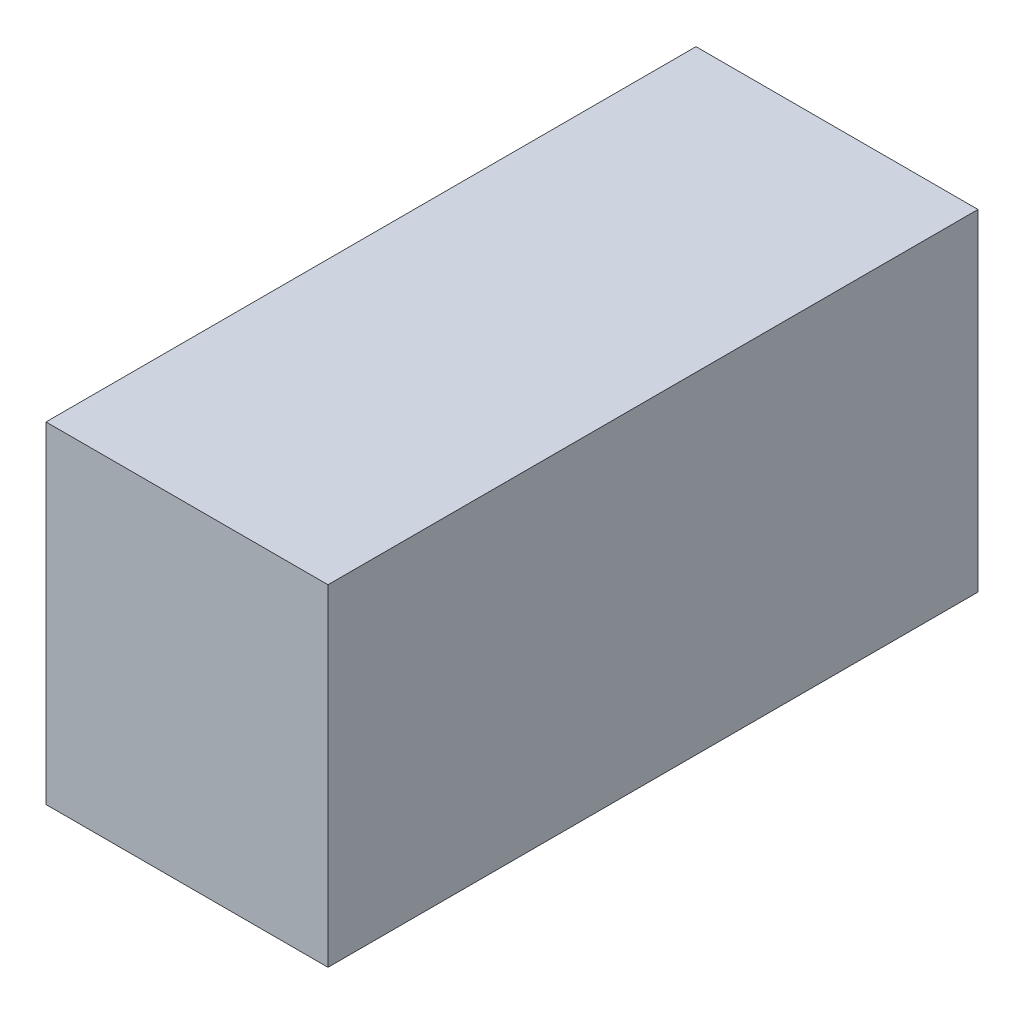
SolidWorks part; units mm, degrees
ref_plane "Front Plane" through (0, 0, 0) normal (0, 0, 1) x (1, 0, 0)
ref_plane "Top Plane" through (0, 0, 0) normal (0, 1, 0) x (1, 0, 0)
ref_plane "Right Plane" through (0, 0, 0) normal (1, 0, 0) x (0, 0, -1)
sketch "Sketch1" plane through (0, 0, 0) normal (0, 0, 1) x (1, 0, 0)
  line L1 (-10, -11.75) -> (10, -11.75)
  line L2 (-10, -11.75) -> (-10, 11.75)
  line L3 (-10, 11.75) -> (10, 11.75)
  line L4 (10, -11.75) -> (10, 11.75)
  line L5 (-10, -11.75) -> (10, 11.75) construction
  line L6 (-10, 11.75) -> (10, -11.75) construction
  point P0 (0, 0)
extrude "Envelope" add sketch "Sketch1" along normal blind 46.1
